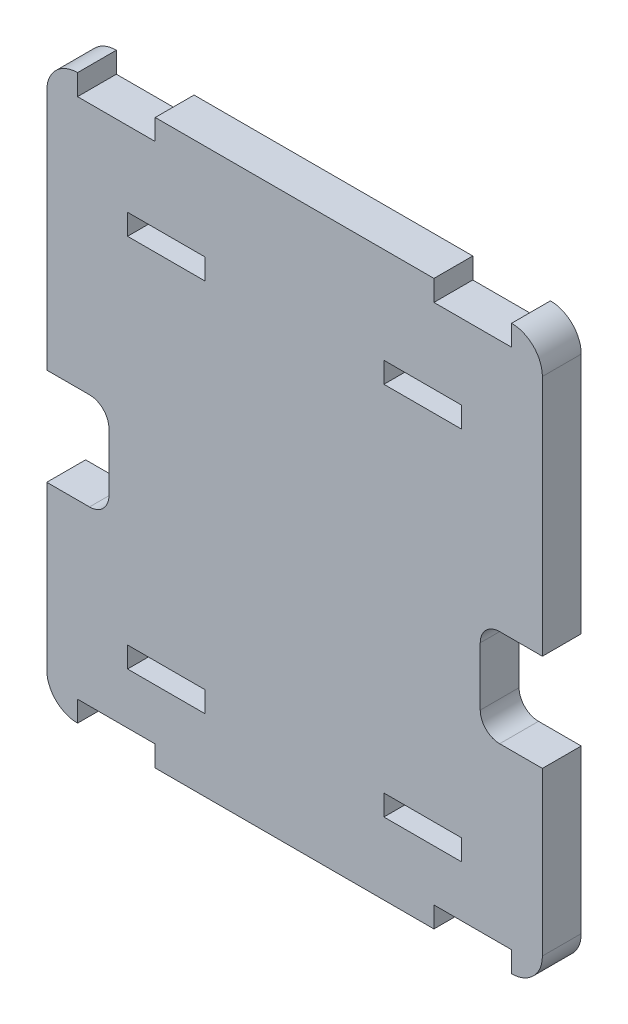
SolidWorks part; units mm, degrees
ref_plane "Front Plane" through (0, 0, 0) normal (0, 0, 1) x (1, 0, 0)
ref_plane "Top Plane" through (0, 0, 0) normal (0, 1, 0) x (1, 0, 0)
ref_plane "Right Plane" through (0, 0, 0) normal (1, 0, 0) x (0, 0, -1)
sketch "Sketch1" plane through (0, 0, 0) normal (0, 0, 1) x (1, 0, 0)
  line L0 (8603.4559, 2991.5485) -> (8603.4559, 2951.9392)
  line L1 (8603.4559, 2936.0642) -> (8603.4559, 2909.4958)
  line L2 (8621.1851, 2996.5777) -> (8666.7527, 2996.5777)
  line L3 (8608.4851, 2993.1741) -> (8621.1851, 2993.1741)
  line L4 (8666.7527, 2993.1741) -> (8679.4527, 2993.1741)
  line L5 (8684.4819, 2991.5485) -> (8684.4819, 2951.9392)
  line L6 (8684.4819, 2936.0642) -> (8684.4819, 2909.4958)
  line L7 (8621.1851, 2904.4666) -> (8666.7527, 2904.4666)
  line L8 (8608.4851, 2907.8702) -> (8621.1851, 2907.8702)
  line L9 (8666.7527, 2907.8702) -> (8679.4527, 2907.8702)
  line L10 (8684.4819, 2951.9392) -> (8677.4969, 2951.9392)
  line L11 (8684.4819, 2936.0642) -> (8677.4969, 2936.0642)
  line L12 (8674.3219, 2948.7642) -> (8674.3219, 2939.2392)
  line L13 (8603.4559, 2951.9392) -> (8610.4409, 2951.9392)
  line L14 (8603.4559, 2936.0642) -> (8610.4409, 2936.0642)
  line L15 (8613.6159, 2948.7642) -> (8613.6159, 2939.2392)
  line L16 (8616.6639, 2919.6304) -> (8616.6639, 2916.2268)
  line L17 (8629.3639, 2919.6304) -> (8629.3639, 2916.2268)
  line L18 (8671.2739, 2919.6304) -> (8671.2739, 2916.2268)
  line L19 (8658.5739, 2919.6304) -> (8658.5739, 2916.2268)
  line L20 (8671.2739, 2977.4916) -> (8671.2739, 2980.8952)
  line L21 (8658.5739, 2977.4916) -> (8658.5739, 2980.8952)
  line L22 (8616.6639, 2977.4916) -> (8616.6639, 2980.8952)
  line L23 (8629.3639, 2977.4916) -> (8629.3639, 2980.8952)
  line L24 (8616.6639, 2980.8952) -> (8629.3639, 2980.8952)
  line L25 (8616.6639, 2977.4916) -> (8629.3639, 2977.4916)
  line L26 (8658.5739, 2980.8952) -> (8671.2739, 2980.8952)
  line L27 (8658.5739, 2977.4916) -> (8671.2739, 2977.4916)
  line L28 (8671.2739, 2916.2268) -> (8658.5739, 2916.2268)
  line L29 (8671.2739, 2919.6304) -> (8658.5739, 2919.6304)
  line L30 (8629.3639, 2916.2268) -> (8616.6639, 2916.2268)
  line L31 (8629.3639, 2919.6304) -> (8616.6639, 2919.6304)
  line L32 (8608.4851, 2993.1741) -> (8608.4851, 2996.5777)
  line L33 (8621.1851, 2993.1741) -> (8621.1851, 2996.5777)
  line L34 (8679.4527, 2993.1741) -> (8679.4527, 2996.5777)
  line L35 (8666.7527, 2993.1741) -> (8666.7527, 2996.5777)
  line L36 (8608.4851, 2907.8702) -> (8608.4851, 2904.4666)
  line L37 (8621.1851, 2907.8702) -> (8621.1851, 2904.4666)
  line L38 (8679.4527, 2907.8702) -> (8679.4527, 2904.4666)
  line L39 (8666.7527, 2907.8702) -> (8666.7527, 2904.4666)
  arc A0 (8608.4851, 2996.5777) -> (8603.4559, 2991.5485) centre (8608.4851, 2991.5485) ccw
  arc A1 (8684.4819, 2991.5485) -> (8679.4527, 2996.5777) centre (8679.4527, 2991.5485) ccw
  arc A2 (8679.4527, 2904.4666) -> (8684.4819, 2909.4958) centre (8679.4527, 2909.4958) ccw
  arc A3 (8603.4559, 2909.4958) -> (8608.4851, 2904.4666) centre (8608.4851, 2909.4958) ccw
  arc A4 (8674.3219, 2939.2392) -> (8677.4969, 2936.0642) centre (8677.4969, 2939.2392) ccw
  arc A5 (8677.4969, 2951.9392) -> (8674.3219, 2948.7642) centre (8677.4969, 2948.7642) ccw
  arc A6 (8610.4409, 2936.0642) -> (8613.6159, 2939.2392) centre (8610.4409, 2939.2392) ccw
  arc A7 (8613.6159, 2948.7642) -> (8610.4409, 2951.9392) centre (8610.4409, 2948.7642) ccw
extrude "Boss-Extrude1" add sketch "Sketch1" along normal blind 6.35
